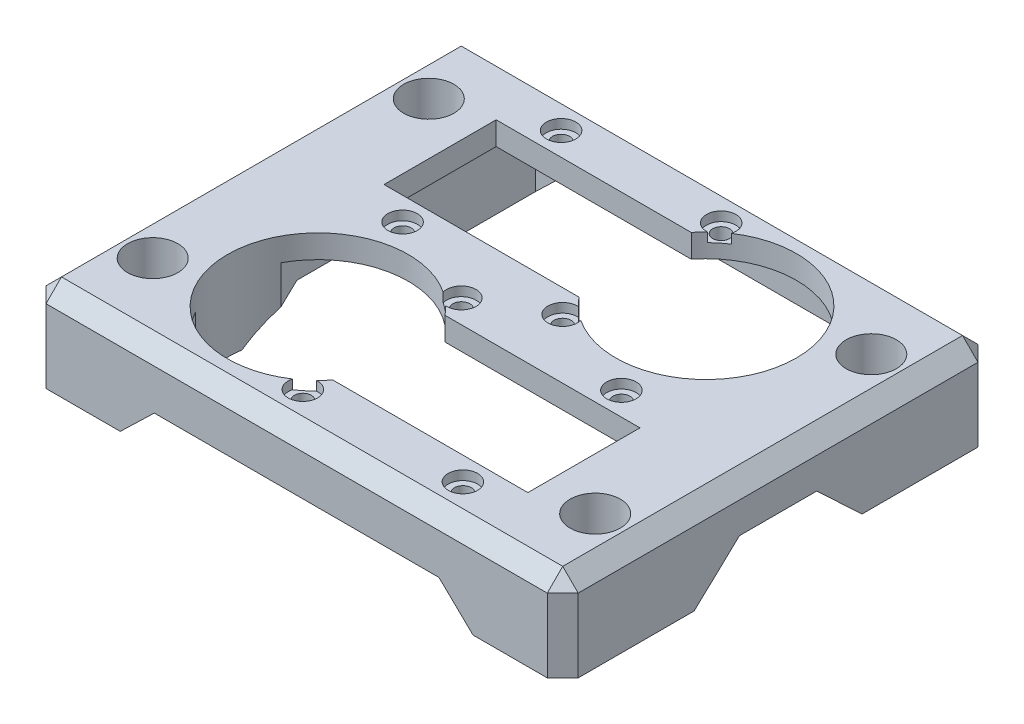
SolidWorks part; units mm, degrees
ref_plane "Plan de face" through (0, 0, 0) normal (0, 0, 1) x (1, 0, 0)
ref_plane "Plan de dessus" through (0, 0, 0) normal (0, 1, 0) x (1, 0, 0)
ref_plane "Plan de droite" through (0, 0, 0) normal (1, 0, 0) x (0, 0, -1)
sketch "Esquisse1" plane through (0, 0, 0) normal (0, 1, 0) x (1, 0, 0)
  line L0 (0, 0) -> (0, 20.5) construction
  line L1 (0, 20.5) -> (20.7, 20.5) construction
  line L2 (20.7, 20.5) -> (20.7, 0) construction
  line L3 (20.7, 0) -> (0, 0) construction
  line L4 (12.3, -4.7) -> (33, -4.7) construction
  line L5 (33, -4.7) -> (33, -25.2) construction
  line L6 (33, -25.2) -> (12.3, -25.2) construction
  line L7 (12.3, -25.2) -> (12.3, -4.7) construction
  line L8 (-5.4, 17.5) -> (19.8297, 17.5)
  line L9 (-5.4, 17.5) -> (-5.4, 3)
  line L10 (-5.4, 3) -> (19.8297, 3)
  line L11 (13.1703, -7.7) -> (38.4, -7.7)
  line L12 (38.4, -7.7) -> (38.4, -22.2)
  line L13 (38.4, -22.2) -> (13.1703, -22.2)
  line L14 (-10.4, 23.5) -> (43.4, 23.5)
  line L15 (43.4, 23.5) -> (43.4, -28.2)
  line L16 (43.4, -28.2) -> (-10.4, -28.2)
  line L17 (-10.4, -28.2) -> (-10.4, 23.5)
  circle A0 centre (0, 20.5) radius 1.1
  circle A1 centre (20.7, 20.5) radius 1.1
  circle A2 centre (20.7, 0) radius 1.1
  circle A3 centre (0, 0) radius 1.1
  circle A4 centre (12.3, -4.7) radius 1.1
  circle A5 centre (33, -4.7) radius 1.1
  circle A6 centre (12.3, -25.2) radius 1.1
  circle A7 centre (33, -25.2) radius 1.1
  circle A8 centre (29, 10.25) radius 11.69
  circle A9 centre (4, -14.95) radius 11.69
  point P22 (0, 10.25)
  point P23 (-5.4, 10.25)
  point P26 (33, -14.95)
  point P27 (12.3, -14.95)
  point P33 (38.4, -14.95)
  dimension "D3" = 2.2
  dimension "D9" = 23.38
  dimension "D1" = 20.7
  dimension "D2" = 20.5
  dimension "D4" = 4.7
  dimension "D5" = 8.4
  dimension "D6" = 14.5
  dimension "D7" = 5.4
  dimension "D8" = 29
  dimension "D10" = 29
  dimension "D11" = 5.4
  dimension "D12" = 3
  dimension "D13" = 3
  dimension "D14" = 5
  dimension "D15" = 5
extrude "Boss.-Extru.1" add sketch "Esquisse1" along normal blind 3 contours L17 L16 L15 L14 A9 L11 L12 L13 A8 L10 L9 L8 A7 A6 A5 A4 A3 A2 A1 A0
hole_wizard "Chambrage pour vis à six pans creux M1.61" positions "Esquisse2" profile "Esquisse3" counterbore size "M1.6" standard "ISO" end condition through all
sketch "Esquisse2" plane through (0, 3, 0) normal (0, 1, 0) x (1, 0, 0)
  point P0 (0, 20.5)
  point P3 (20.7, 20.5)
  point P6 (20.7, 0)
  point P9 (12.3, -4.7)
  point P12 (0, 0)
  point P15 (33, -4.7)
  point P18 (12.3, -25.2)
  point P21 (33, -25.2)
sketch "Esquisse3" plane through (0, 3, -20.5) normal (1, 0, 0) x (0, 0, 1)
  line L0 (0, 0) -> (0, 3)
  line L1 (0, 3) -> (1.1, 3)
  line L3 (1.1, 3) -> (1.1, 1.2)
  line L4 (1.1, 1.2) -> (1.9, 1.2)
  line L5 (1.9, 1.2) -> (1.9, 0)
  line L7 (1.9, 0) -> (0, 0)
  line L11 (0, -6.35) -> (0, 107.95) construction
  dimension "Diamètre du perçage jusqu'au prochain" = 2.2
  dimension "Profondeur du perçage jusqu'au prochain" = 3
  dimension "Diamètre du chambrage" = 3.8
  dimension "Profondeur du chambrage" = 1.2
sketch "Esquisse4" plane through (0, 0, 0) normal (0, -1, 0) x (1, 0, 0)
  line L5 (-10.4, 28.2) -> (-17.91, 28.2)
  line L6 (-17.91, 28.2) -> (-17.91, -23.5)
  line L7 (-17.91, -23.5) -> (-10.4, -23.5)
  line L8 (-6.31, 28.2) -> (-6.31, 20.46)
  line L9 (43.4, 28.2) -> (-10.4, 28.2) construction
  line L10 (-10.4, -23.5) -> (43.4, -23.5) construction
  line L11 (-10.4, 28.2) -> (-6.31, 28.2)
  line L12 (-10.4, -23.5) -> (-6.31, -23.5)
  line L13 (-6.31, 20.46) -> (-6.31, 9.44) construction
  line L14 (-6.31, 9.44) -> (-6.31, -23.5)
  line L16 (43.4, -23.5) -> (43.4, 28.2) construction
  line L17 (39.31, 28.2) -> (50.91, 28.2)
  line L18 (39.31, 28.2) -> (39.31, -4.74)
  line L19 (39.31, -23.5) -> (50.91, -23.5)
  line L20 (50.91, 28.2) -> (50.91, -23.5)
  line L21 (39.31, -4.74) -> (39.31, -15.76) construction
  line L22 (39.31, -15.76) -> (39.31, -23.5)
  arc A0 (13.1703, 22.2) -> (13.1703, 7.7) centre (4, 14.95) ccw construction
  arc A1 (13.1703, 22.2) -> (13.1703, 7.7) centre (4, 14.95) ccw
  arc A2 (19.8297, -17.5) -> (19.8297, -3) centre (29, -10.25) ccw construction
  arc A3 (39.31, -15.76) -> (39.31, -4.74) centre (29, -10.25) ccw
  arc A4 (39.31, -4.74) -> (19.8297, -3) centre (29, -10.25) ccw construction
  arc A5 (19.8297, -17.5) -> (39.31, -15.76) centre (29, -10.25) ccw construction
  arc M5 (13.1703, 7.7) -> (13.1703, 22.2) centre (4, 14.95) cw
  line M21 (-10.4, 28.2) -> (-10.4, -23.5)
  line M22 (-10.4, -23.5) -> (43.4, -23.5)
  line M24 (43.4, 28.2) -> (-10.4, 28.2)
  dimension "D1" = 4.09
  dimension "D2" = 11.6
  dimension "D3" = 4.09
  dimension "D4" = 11.6
extrude "Boss.-Extru.2" add sketch "Esquisse4" along normal blind 19 from surface at -3 contours L14 L8 M5 M24 M21 M22 | L6 L7 L5 M21 | L17 L20 L19 L22 A3 L18 starting at face at (0, 3, -18.6)
sketch "Esquisse6" plane through (0, 3, 0) normal (0, 1, 0) x (1, 0, 0)
  line L0 (-17.91, 15.5) -> (-6.31, 15.5) construction
  line L1 (-17.91, 23.5) -> (-17.91, -28.2) construction
  line L3 (-17.91, 23.5) -> (50.91, 23.5) construction
  line L4 (-6.31, 23.5) -> (-6.31, -9.44) construction
  line L5 (-17.91, -2.35) -> (-36.3975, -2.35) construction
  line L6 (16.5, 23.5) -> (16.5, 35.2251) construction
  line L7 (-17.91, 23.5) -> (50.91, 23.5) construction
  circle A0 centre (-12.11, 15.5) radius 1.6
  circle A1 centre (-12.11, -20.2) radius 1.6
  circle A2 centre (45.11, -20.2) radius 1.6
  circle A3 centre (45.11, 15.5) radius 1.6
  dimension "D1" = 3.2
  dimension "D2" = 8
extrude "Enlèv. mat.-Extru.2" cut sketch "Esquisse6" against normal through all
hole_wizard "Chambrage pour vis à six pans creux M31" positions "Esquisse7" profile "Esquisse8" counterbore size "M3" standard "ISO" end condition through all
sketch "Esquisse7" plane through (0, 3, 0) normal (0, 1, 0) x (1, 0, 0)
  point P0 (-12.11, 15.5)
  point P3 (-12.11, -20.2)
  point P7 (45.11, 15.5)
  point P10 (45.11, -20.2)
sketch "Esquisse8" plane through (-12.11, 3, -15.5) normal (1, 0, 0) x (0, 0, 1)
  line L0 (0, 0) -> (0, 19)
  line L1 (0, 19) -> (1.6, 19)
  line L3 (1.6, 19) -> (1.6, 7)
  line L4 (1.6, 7) -> (3.25, 7)
  line L5 (3.25, 7) -> (3.25, 0)
  line L7 (3.25, 0) -> (0, 0)
  line L11 (0, -6.35) -> (0, 107.95) construction
  dimension "Diamètre du perçage jusqu'au prochain" = 3.2
  dimension "Profondeur du perçage jusqu'au prochain" = 19
  dimension "Diamètre du chambrage" = 6.5
  dimension "Profondeur du chambrage" = 7
sketch "Esquisse9" plane through (-17.91, 0, 0) normal (-1, 0, 0) x (0, 0, 1)
  line L1 (-23.5, -16) -> (28.2, -16) construction
  line L3 (2.35, -16) -> (2.35, -38.5504) construction
  line L6 (-23.5, -8.5) -> (-8.5, -8.5)
  line L7 (13.2, -8.5) -> (7.35, -3)
  line L8 (-23.5, -16) -> (-23.5, 3) construction
  line L9 (-8.5, -8.5) -> (-2.65, -3)
  line L10 (-2.65, -3) -> (7.35, -3)
  line L11 (-23.5, 3) -> (28.2, 3) construction
  line L12 (28.2, -8.5) -> (13.2, -8.5)
  line L13 (28.2, -16) -> (28.2, 3) construction
  line L14 (-23.5, -16) -> (-23.5, -8.5)
  line L15 (-23.5, -16) -> (28.2, -16)
  line L16 (28.2, -16) -> (28.2, -8.5)
  point P16 (2.35, -3)
  dimension "D1" = 7.5
  dimension "D2" = 6
  dimension "D3" = 15
  dimension "D4" = 5
extrude "Enlèv. mat.-Extru.3" cut sketch "Esquisse9" against normal through all both and the other way through all
ref_plane "Plan1" through (0, 0, 2.35) normal (0, 0, 1) x (1, 0, 0)
sketch "Esquisse10" plane through (0, 0, 28.2) normal (0, 0, 1) x (1, 0, 0)
  line L0 (-6.31, -8.5) -> (-1.905, -4.25)
  line L1 (39.31, 0) -> (-6.31, 0) construction
  line L2 (16.5, 3) -> (16.5, 17.7438) construction
  line L3 (50.91, 3) -> (-17.91, 3) construction
  line L4 (39.31, -8.5) -> (34.905, -4.25)
  line L5 (-1.905, -4.25) -> (34.905, -4.25)
  line L6 (34.905, -4.25) -> (30.5, 0) construction
  line L7 (-1.905, -4.25) -> (2.5, 0) construction
  line L13 (39.31, -8.5) -> (50.91, -8.5)
  line L14 (50.91, -8.5) -> (50.91, 3)
  line L15 (50.91, 3) -> (-17.91, 3)
  line L16 (-17.91, 3) -> (-17.91, -8.5)
  line L17 (-17.91, -8.5) -> (-6.31, -8.5)
  line L18 (-6.31, -8.5) -> (-6.31, 0)
  line L19 (-6.31, 0) -> (39.31, 0)
  line L20 (39.31, 0) -> (39.31, -8.5)
  line L21 (39.31, -8.5) -> (50.91, -8.5)
  line L22 (50.91, -8.5) -> (50.91, 3)
  line L23 (50.91, 3) -> (-17.91, 3)
  line L24 (-17.91, 3) -> (-17.91, -8.5)
  line L25 (-17.91, -8.5) -> (-6.31, -8.5)
  line L27 (2.5, 0) -> (30.5, 0) construction
  dimension "D1" = 28
  dimension "D3" = 7.25
  dimension "D2" = 0
extrude "Boss.-Extru.3" add sketch "Esquisse10" along normal blind 2
mirror "Symétrie1" about plane through (0, 0, 2.35) normal (0, 0, 1) of "Boss.-Extru.3"
chamfer "Chanfrein1" distance 2 angle 45 8 edges at (50.91, 3, 2.35) (-17.91, 3, 2.35) (-17.91, -2.75, -25.5) (50.91, -2.75, -25.5) (50.91, -2.75, 30.2) (16.5, 3, 30.2) (16.5, 3, -25.5) (-17.91, -2.75, 30.2)
